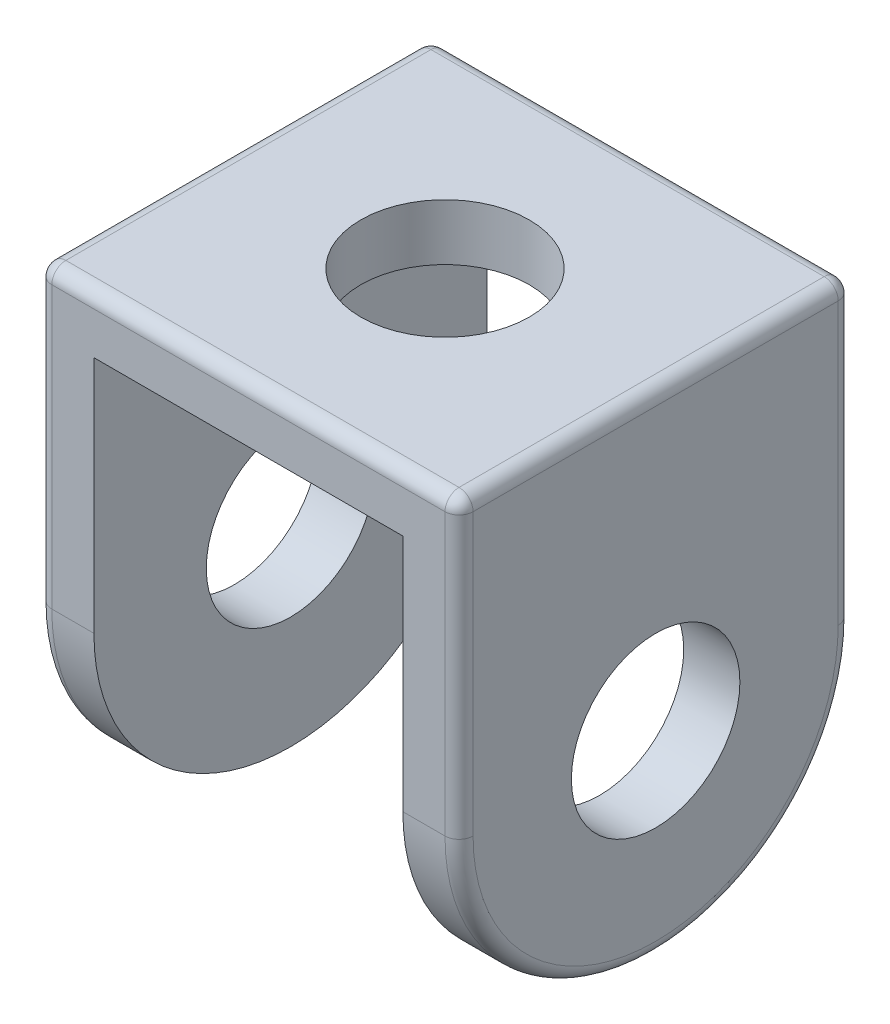
SolidWorks part; units mm, degrees
material "1060 合金"
ref_plane "前视基准面" through (0, 0, 0) normal (0, 0, 1) x (1, 0, 0)
ref_plane "上视基准面" through (0, 0, 0) normal (0, 1, 0) x (1, 0, 0)
ref_plane "右视基准面" through (0, 0, 0) normal (1, 0, 0) x (0, 0, -1)
sketch "草图1" plane through (0, 0, 0) normal (1, 0, 0) x (0, 0, -1)
  line L0 (0, 0) -> (0, -21)
  line L1 (28, -21) -> (28, 0)
  line L2 (28, 0) -> (0, 0)
  arc A0 (0, -21) -> (28, -21) centre (14, -21) ccw
  circle A1 centre (14, -21) radius 6
  dimension "D1" = 14
  dimension "D3" = 12
  dimension "D2" = 21
extrude "拉伸1" add sketch "草图1" along normal blind 30
sketch "草图2" plane through (0, 0, 0) normal (0, 0, 1) x (1, 0, 0)
  line L0 (0, -35) -> (30, -35) construction
  line L1 (4, -4) -> (26, -4)
  line L2 (4, -4) -> (4, -35)
  line L3 (4, -35) -> (26, -35)
  line L4 (26, -4) -> (26, -35)
  line L5 (30, 0) -> (0, 0) construction
  line L6 (0, 0) -> (0, -21) construction
  line L7 (30, 0) -> (30, -21) construction
  point P8 (0, -10.5)
  dimension "D1" = 4
  dimension "D2" = 4
  dimension "D3" = 4
extrude "拉伸2" cut sketch "草图2" against normal through all
sketch "草图3" plane through (0, 0, 0) normal (0, 1, 0) x (1, 0, 0)
  line L0 (0, 28) -> (30, 0) construction
  circle A0 centre (15, 14) radius 6
  dimension "D1" = 12
extrude "拉伸3" cut sketch "草图3" against normal blind 30
fillet "圆角1" radius 1 10 edges at (0, -10.5, -28) (0, -35, -14) (30, -10.5, -28) (30, -35, -14) (0, -10.5, 0) (30, -10.5, 0) (30, 0, -14) (15, 0, -28) (0, 0, -14) (15, 0, 0)
